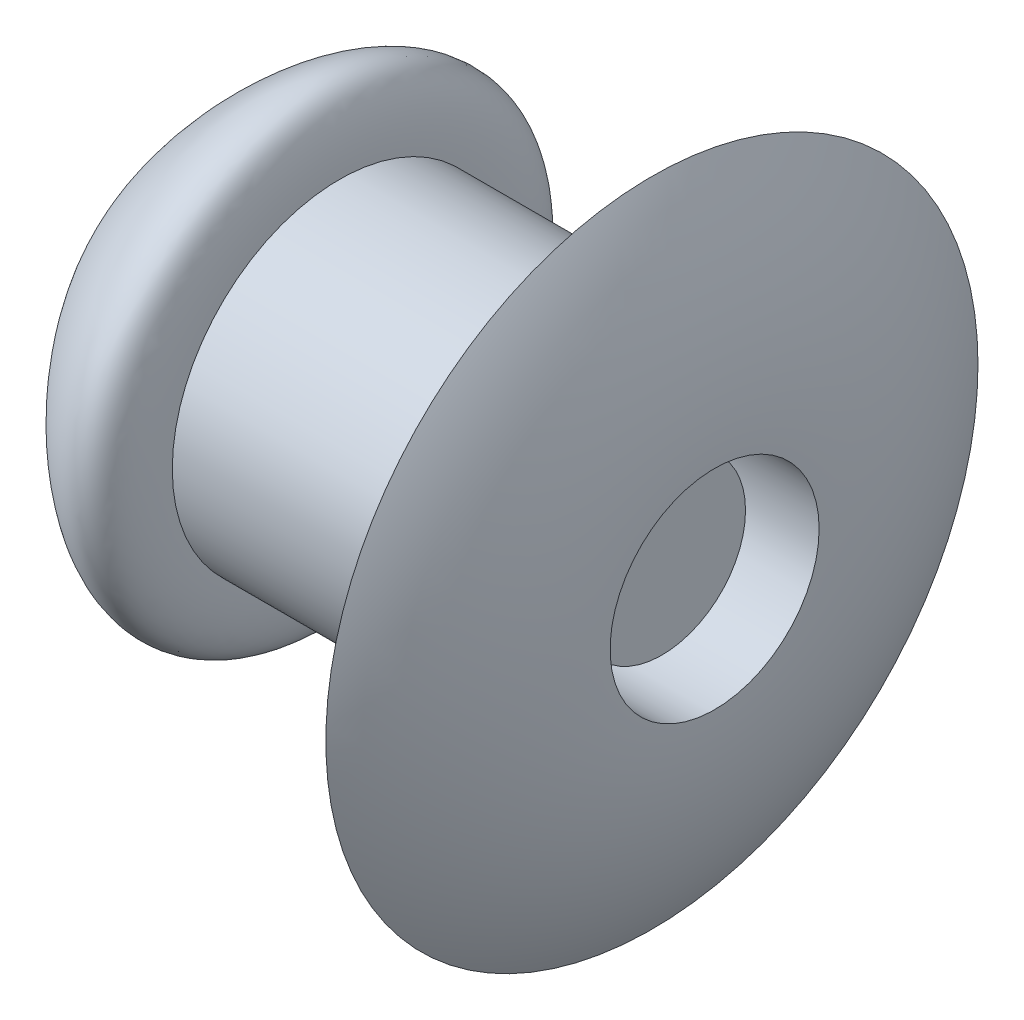
SolidWorks part; units mm, degrees
material "AISI 316 Arkusz stali nierdzewnej (SS)"
ref_plane "Płaszczyzna przednia" through (0, 0, 0) normal (0, 0, 1) x (1, 0, 0)
ref_plane "Płaszczyzna górna" through (0, 0, 0) normal (0, 1, 0) x (1, 0, 0)
ref_plane "Płaszczyzna prawa" through (0, 0, 0) normal (1, 0, 0) x (0, 0, -1)
sketch "Szkic1" plane through (0, 0, 0) normal (0, 0, 1) x (1, 0, 0)
  line L0 (350.8561, 893.6816) -> (345.4, 893.6816)
  line L1 (351.4866, 894.9316) -> (347, 894.9316)
  line L2 (347, 894.9316) -> (347, 894.6816)
  line L3 (347, 894.6816) -> (350.8561, 894.6816)
  line L4 (350.8561, 894.6816) -> (350.8561, 893.6816)
  line L5 (350.7366, 897.5816) -> (350.7366, 895.6816)
  line L6 (350.7366, 895.6816) -> (347, 895.6816)
  line L7 (350.8561, 893.6816) -> (345.4, 893.6816) construction
  line L8 (350.8561, 893.6816) -> (345.4, 893.6816) construction
  line L9 (351.4866, 893.6816) -> (350.8561, 893.6816) construction
  line L10 (350.7366, 521.1816) -> (350.7366, 901.1816) construction
  line L11 (347, 4.3583) -> (347, 898.0048) construction
  arc A0 (351.4866, 894.9316) -> (350.7366, 897.5816) centre (346.4299, 894.9316) ccw
  spline S0 degree 3 poles (347, 895.6816) (347.0366, 898.0214) (343.5366, 893.3094) (345.7587, 895.1701) (346.0554, 894.8565) knots 0 0 0 0 0.744502 1 1 1 1
  spline S1 degree 2 poles (346.0554, 894.8565) (345.1739, 894.872) (345.4, 893.6816) knots 0 0 0 1 1 1
  point P4 (345.4445, 893.6816)
  dimension "D18" = 4.8231
  dimension "D1" = 2
  dimension "D2" = 0.1195
  dimension "D3" = 4
  dimension "D4" = 2.5
  dimension "D5" = 0.75
  dimension "D6" = 7.8
  dimension "D7" = 0.9668
  dimension "D8" = 1.1117
  dimension "D9" = 1.175
  dimension "D10" = 1.2811
  dimension "D11" = 2.7999
  dimension "D12" = 0.4548
  dimension "D13" = 0.9446
  dimension "D14" = 1.1893
  dimension "D15" = 1.3067
  dimension "D16" = 2.0033
  dimension "D17" = 1.6
revolve "Obrót1" add sketch "Szkic1" angle 360 about L7
